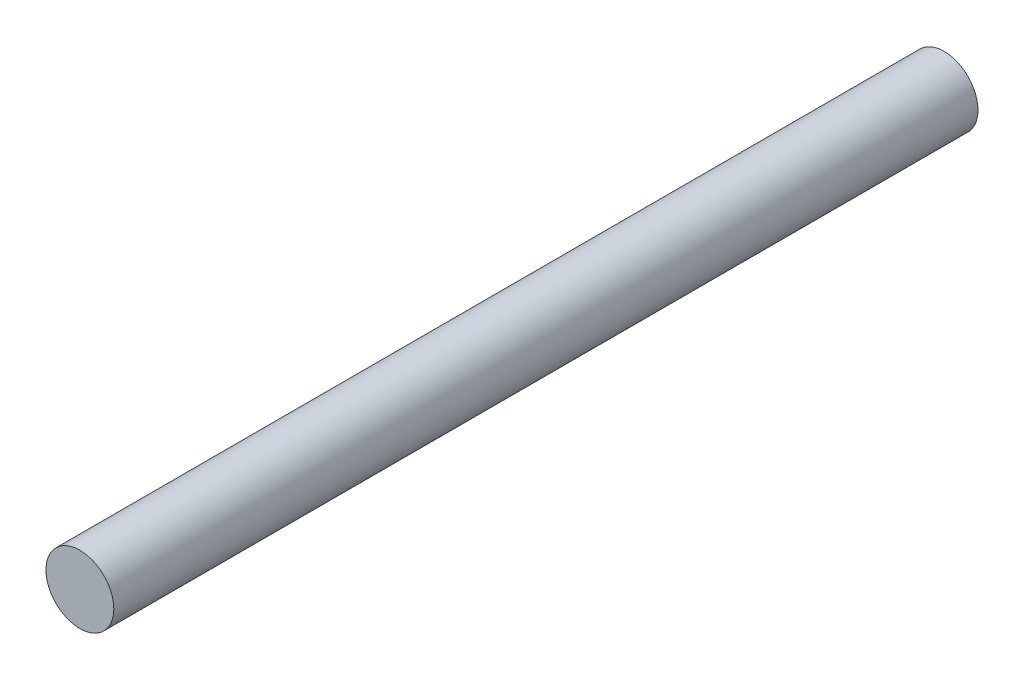
SolidWorks part; units mm, degrees
ref_plane "Front Plane" through (0, 0, 0) normal (0, 0, 1) x (1, 0, 0)
ref_plane "Top Plane" through (0, 0, 0) normal (0, 1, 0) x (1, 0, 0)
ref_plane "Right Plane" through (0, 0, 0) normal (1, 0, 0) x (0, 0, -1)
sketch "Sketch1" plane through (0, 0, 0) normal (0, 0, 1) x (1, 0, 0)
  circle A0 centre (0, 0) radius 8.89
  dimension "D1" = 17.78
extrude "Boss-Extrude1" add sketch "Sketch1" along normal blind 173.2 and the other way blind 53.2
